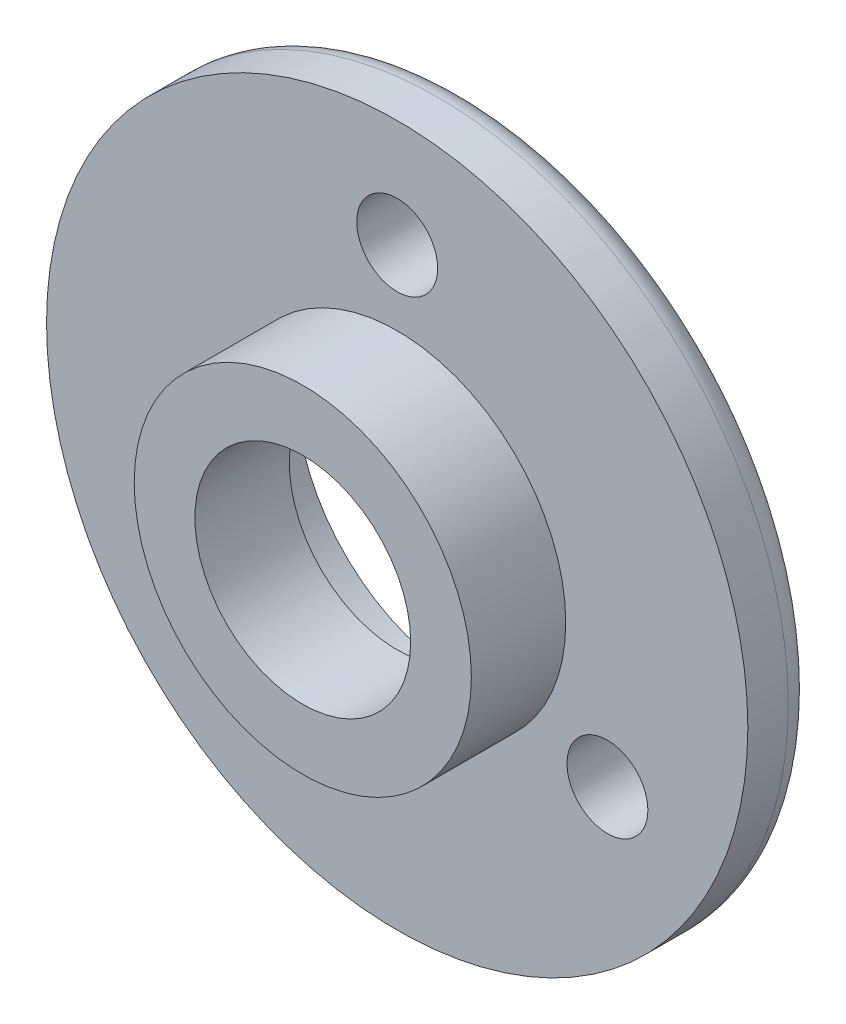
SolidWorks part; units mm, degrees
ref_plane "Front Plane" through (0, 0, 0) normal (0, 0, 1) x (1, 0, 0)
ref_plane "Top Plane" through (0, 0, 0) normal (0, 1, 0) x (1, 0, 0)
ref_plane "Right Plane" through (0, 0, 0) normal (1, 0, 0) x (0, 0, -1)
sketch "Sketch1" plane through (0, 0, 0) normal (0, 0, 1) x (1, 0, 0)
  circle A0 centre (0, 0) radius 26
  dimension "D1" = 52
extrude "Boss-Extrude1" add sketch "Sketch1" along normal blind 5
sketch "Sketch2" plane through (0, 0, 5) normal (0, 0, 1) x (1, 0, 0)
  circle A0 centre (0, 0) radius 12.5
  dimension "D1" = 25
extrude "Boss-Extrude2" add sketch "Sketch2" along normal blind 7
sketch "Sketch3" plane through (0, 0, 12) normal (0, 0, 1) x (1, 0, 0)
  circle A0 centre (0, 0) radius 8
  dimension "D1" = 16
extrude "Cut-Extrude1" cut sketch "Sketch3" against normal through all
sketch "Sketch4" plane through (0, 0, 5) normal (0, 0, 1) x (1, 0, 0)
  line L0 (0, 0) -> (0, 26) construction
  circle A0 centre (0, 0) radius 26 construction
  circle A1 centre (0, 18) radius 3
  circle A2 centre (0, 0) radius 26 construction
  circle A3 centre (0, 0) radius 26 construction
  circle A4 centre (15.5885, -9) radius 3
  circle A5 centre (0, 0) radius 26 construction
  circle A6 centre (-15.5885, -9) radius 3
  circle A7 centre (0, 0) radius 12.5
  point P17 (0, 0)
  dimension "D1" = 6
  dimension "D2" = 18
  dimension "D3" = 3
extrude "Cut-Extrude2" cut sketch "Sketch4" against normal through all
fillet "Fillet3" radius 2 1 edges at (26, 0, 0)
